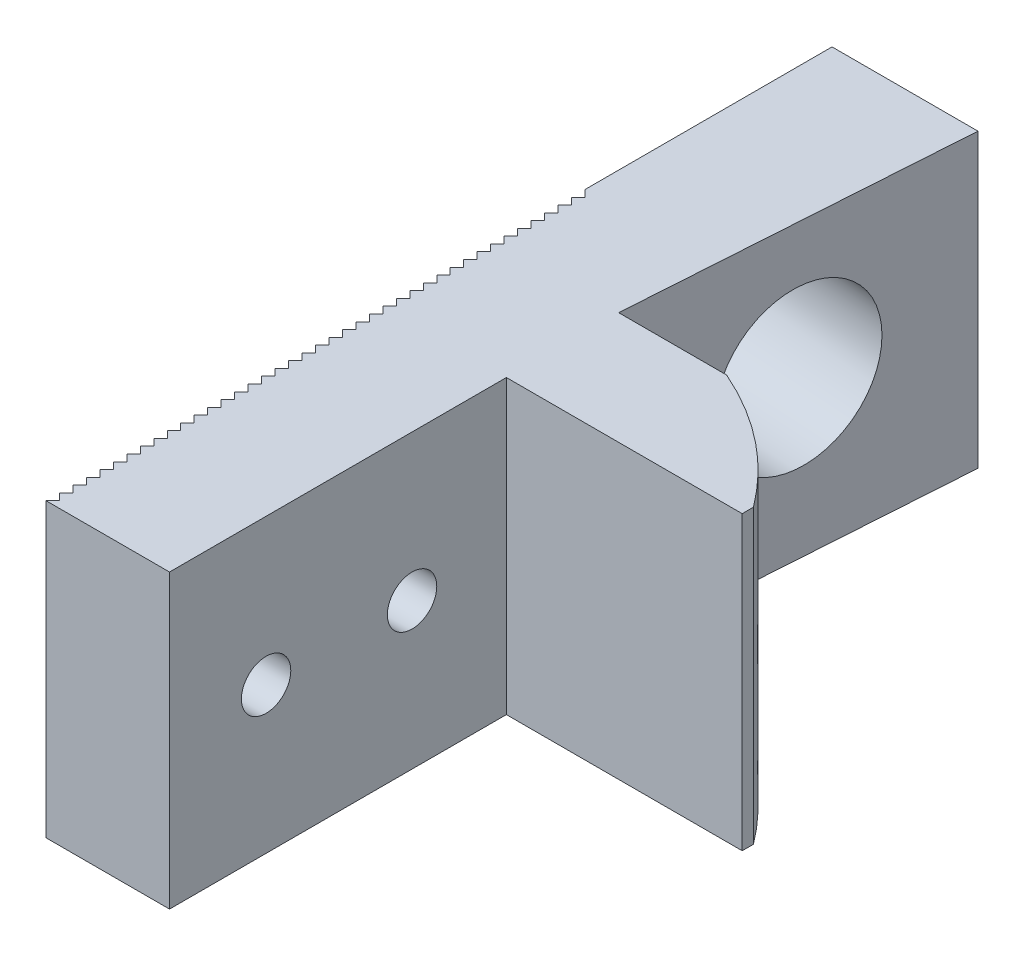
SolidWorks part; units mm, degrees
ref_plane "前视基准面" through (0, 0, 0) normal (0, 0, 1) x (1, 0, 0)
ref_plane "上视基准面" through (0, 0, 0) normal (0, 1, 0) x (1, 0, 0)
ref_plane "右视基准面" through (0, 0, 0) normal (1, 0, 0) x (0, 0, -1)
sketch "草图1" plane through (0, 0, 0) normal (0, 1, 0) x (1, 0, 0)
  line L1 (0, 35) -> (6.5, 35)
  line L2 (6.5, 35) -> (5.5, 20)
  line L6 (5.5, 15) -> (5.5, 0)
  line L7 (5.5, 0) -> (0, 0)
  line L8 (5.5, 20) -> (10.3063, 20)
  line L10 (16, 15.5) -> (16, 15)
  line L11 (16, 15) -> (5.5, 15)
  line L48 (0, 24) -> (0, 35)
  line L70 (0.3, 0.3) -> (0, 0)
  line L71 (0, 0.6) -> (0.3, 0.3)
  line L72 (0, 24) -> (0.3, 23.7)
  line L83 (0.3, 0.9) -> (0, 0.6)
  line L84 (0, 1.2) -> (0.3, 0.9)
  line L85 (0.3, 1.5) -> (0, 1.2)
  line L86 (0, 1.8) -> (0.3, 1.5)
  line L87 (0.3, 2.1) -> (0, 1.8)
  line L88 (0, 2.4) -> (0.3, 2.1)
  line L89 (0.3, 2.7) -> (0, 2.4)
  line L90 (0, 3) -> (0.3, 2.7)
  line L91 (0.3, 3.3) -> (0, 3)
  line L92 (0, 3.6) -> (0.3, 3.3)
  line L93 (0.3, 3.9) -> (0, 3.6)
  line L94 (0, 4.2) -> (0.3, 3.9)
  line L95 (0.3, 4.5) -> (0, 4.2)
  line L96 (0, 4.8) -> (0.3, 4.5)
  line L97 (0.3, 5.1) -> (0, 4.8)
  line L98 (0, 5.4) -> (0.3, 5.1)
  line L99 (0.3, 5.7) -> (0, 5.4)
  line L100 (0, 6) -> (0.3, 5.7)
  line L101 (0.3, 6.3) -> (0, 6)
  line L102 (0, 6.6) -> (0.3, 6.3)
  line L103 (0.3, 6.9) -> (0, 6.6)
  line L104 (0, 7.2) -> (0.3, 6.9)
  line L105 (0.3, 7.5) -> (0, 7.2)
  line L106 (0, 7.8) -> (0.3, 7.5)
  line L107 (0.3, 8.1) -> (0, 7.8)
  line L108 (0, 8.4) -> (0.3, 8.1)
  line L109 (0.3, 8.7) -> (0, 8.4)
  line L110 (0, 9) -> (0.3, 8.7)
  line L111 (0.3, 9.3) -> (0, 9)
  line L112 (0, 9.6) -> (0.3, 9.3)
  line L113 (0.3, 9.9) -> (0, 9.6)
  line L114 (0, 10.2) -> (0.3, 9.9)
  line L115 (0.3, 10.5) -> (0, 10.2)
  line L116 (0, 10.8) -> (0.3, 10.5)
  line L117 (0.3, 11.1) -> (0, 10.8)
  line L118 (0, 11.4) -> (0.3, 11.1)
  line L119 (0.3, 11.7) -> (0, 11.4)
  line L120 (0, 12) -> (0.3, 11.7)
  line L121 (0.3, 12.3) -> (0, 12)
  line L122 (0, 12.6) -> (0.3, 12.3)
  line L123 (0.3, 12.9) -> (0, 12.6)
  line L124 (0, 13.2) -> (0.3, 12.9)
  line L125 (0.3, 13.5) -> (0, 13.2)
  line L126 (0, 13.8) -> (0.3, 13.5)
  line L127 (0.3, 14.1) -> (0, 13.8)
  line L128 (0, 14.4) -> (0.3, 14.1)
  line L129 (0.3, 14.7) -> (0, 14.4)
  line L130 (0, 15) -> (0.3, 14.7)
  line L131 (0.3, 15.3) -> (0, 15)
  line L132 (0, 15.6) -> (0.3, 15.3)
  line L133 (0.3, 15.9) -> (0, 15.6)
  line L134 (0, 16.2) -> (0.3, 15.9)
  line L135 (0.3, 16.5) -> (0, 16.2)
  line L136 (0, 16.8) -> (0.3, 16.5)
  line L137 (0.3, 17.1) -> (0, 16.8)
  line L138 (0, 17.4) -> (0.3, 17.1)
  line L139 (0.3, 17.7) -> (0, 17.4)
  line L140 (0, 18) -> (0.3, 17.7)
  line L141 (0.3, 18.3) -> (0, 18)
  line L142 (0, 18.6) -> (0.3, 18.3)
  line L143 (0.3, 18.9) -> (0, 18.6)
  line L144 (0, 19.2) -> (0.3, 18.9)
  line L145 (0.3, 19.5) -> (0, 19.2)
  line L146 (0, 19.8) -> (0.3, 19.5)
  line L147 (0.3, 20.1) -> (0, 19.8)
  line L148 (0, 20.4) -> (0.3, 20.1)
  line L149 (0.3, 20.7) -> (0, 20.4)
  line L150 (0, 21) -> (0.3, 20.7)
  line L151 (0.3, 21.3) -> (0, 21)
  line L152 (0, 21.6) -> (0.3, 21.3)
  line L153 (0.3, 21.9) -> (0, 21.6)
  line L154 (0, 22.2) -> (0.3, 21.9)
  line L155 (0.3, 22.5) -> (0, 22.2)
  line L156 (0, 22.8) -> (0.3, 22.5)
  line L157 (0.3, 23.1) -> (0, 22.8)
  line L158 (0, 23.4) -> (0.3, 23.1)
  line L159 (0.3, 23.7) -> (0, 23.4)
  line L161 (0, 24) -> (0.3, 23.7) [skipped]
  spline S0 degree 2 poles (10.3063, 20) (13.7621, 18.4835) (16, 15.5) knots 0 0 0 1 1 1
  dimension "D1" = 24
  dimension "D2" = 5.5
  dimension "D3" = 45
  dimension "D4" = 90
  dimension "D5" = 0.5
  dimension "D6" = 0.6
  dimension "D7" = 5
  dimension "D8" = 6.5
  dimension "D9" = 40
extrude "凸台-拉伸1" add sketch "草图1" along normal blind 13
sketch "草图4" plane through (4.1482, 0, 0.2765) normal (0.9978, 0, 0.0665) x (0.0665, 0, -0.9978)
  line L0 (27.8382, 13) -> (27.8382, -0.8467) construction
  line L1 (20.3216, 13) -> (35.3549, 13) construction
  line L2 (35.3549, 6.5) -> (23.6718, 6.5) construction
  line L3 (35.3549, 13) -> (35.3549, 0) construction
  circle A0 centre (27.8382, 7) radius 3.5
  dimension "D1" = 7
extrude "切除-拉伸3" cut sketch "草图4" against normal through all
sketch "草图5" plane through (5.5, 0, 0) normal (1, 0, 0) x (0, 0, -1)
  line L0 (0, 6.5) -> (15, 6.5) construction
  line L1 (0, 13) -> (0, 0) construction
  line L2 (15, 13) -> (15, 0) construction
  circle A0 centre (10.8, 6.5) radius 1.1
  circle A1 centre (4.3, 6.5) radius 1.1
  dimension "D1" = 2.2
  dimension "D2" = 4.2
  dimension "D3" = 2.2
  dimension "D4" = 6.5
extrude "切除-拉伸4" cut sketch "草图5" against normal blind 10
